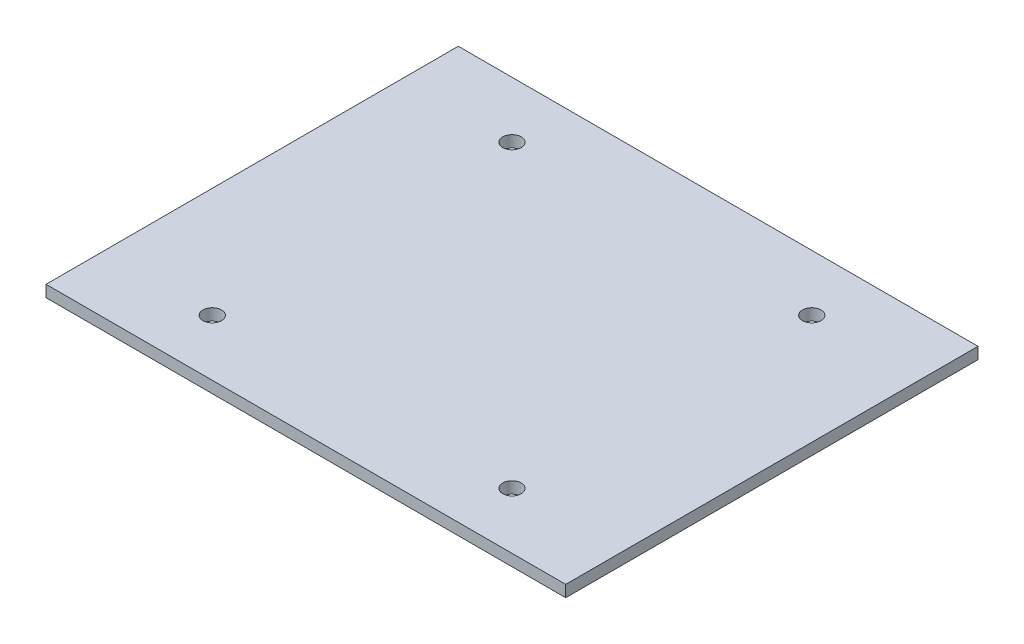
SolidWorks part; units mm, degrees
ref_plane "Front Plane" through (0, 0, 0) normal (0, 0, 1) x (1, 0, 0)
ref_plane "Top Plane" through (0, 0, 0) normal (0, 1, 0) x (1, 0, 0)
ref_plane "Right Plane" through (0, 0, 0) normal (1, 0, 0) x (0, 0, -1)
sketch "Sketch1" plane through (0, 0, 0) normal (0, 1, 0) x (1, 0, 0)
  line L0 (48.075, -47.6977) -> (-61.425, -47.6977) construction
  line L3 (-6.675, -89.1977) -> (-6.675, -6.1977) construction
  line L5 (-6.675, -47.6977) -> (19.1344, -73.5071) construction
  line L6 (-6.675, -47.6977) -> (-32.4844, -73.5071) construction
  line L7 (-6.675, -47.6977) -> (-32.4844, -21.8883) construction
  line L8 (-6.675, -47.6977) -> (19.1344, -21.8883) construction
  line L10 (38.075, -83.1977) -> (-51.425, -83.1977)
  line L11 (38.075, -83.1977) -> (38.075, -12.1977)
  line L12 (38.075, -12.1977) -> (-51.425, -12.1977)
  line L13 (-51.425, -83.1977) -> (-51.425, -12.1977)
  circle A0 centre (-6.675, -47.6977) radius 36.5 construction
  circle A1 centre (19.1344, -73.5071) radius 1.6
  circle A2 centre (-32.4844, -73.5071) radius 1.6
  circle A3 centre (-32.4844, -21.8883) radius 1.6
  circle A4 centre (19.1344, -21.8883) radius 1.6
  circle A5 centre (-6.675, -47.6977) radius 38.1 construction
  dimension "D1" = 73
  dimension "D5" = 3.2
  dimension "D2" = 45
  dimension "D3" = 90
  dimension "D4" = 90
  dimension "D6" = 71
  dimension "D7" = 89.5
  dimension "D8" = 18.9406
  dimension "D9" = 9.6906
extrude "Boss-Extrude1" add sketch "Sketch1" along normal blind 2
